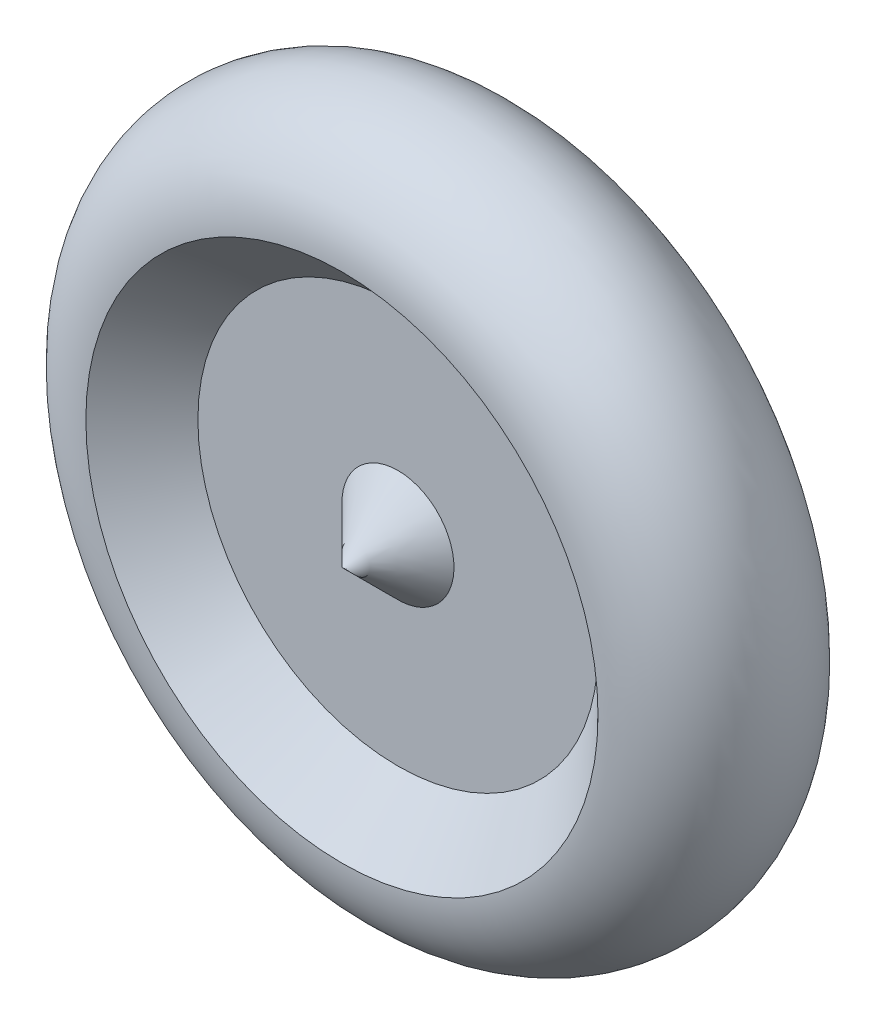
SolidWorks part; units mm, degrees
material "Plain Carbon Steel"
ref_plane "Front Plane" through (0, 0, 0) normal (0, 0, 1) x (1, 0, 0)
ref_plane "Top Plane" through (0, 0, 0) normal (0, 1, 0) x (1, 0, 0)
ref_plane "Right Plane" through (0, 0, 0) normal (1, 0, 0) x (0, 0, -1)
sketch "Sketch2" plane through (0, 0, 0) normal (1, 0, 0) x (0, 0, -1)
  line L0 (0, 0) -> (0, 123.8288) construction
  line L1 (30, 0) -> (-30, 0)
  line L2 (-30, 0) -> (-12.5, 17.5)
  line L3 (-12.5, 17.5) -> (-12.5, 62.5)
  line L4 (-12.5, 62.5) -> (-30, 80)
  line L5 (-30, 80) -> (-26.8319, 79.3853)
  line L6 (0, 110) -> (0, 0)
  line L7 (12.5, 62.5) -> (30, 80)
  line L8 (12.5, 17.5) -> (12.5, 62.5)
  line L9 (30, 0) -> (12.5, 17.5)
  arc A1 (-30, 80) -> (30, 80) centre (0, 80) cw
  point P6 (0, 0)
  point P9 (0, 0)
  point P14 (0, 0)
  point P17 (0, 0)
  point P18 (0, 0)
  point P19 (0, 0)
  point P20 (0, 0)
  dimension "D6" = 30
  dimension "D1" = 45
  dimension "D2" = 80
  dimension "D3" = 135
  dimension "D4" = 135
  dimension "D5" = 60
  dimension "D7" = 60
  dimension "D8" = 80
revolve "Revolve1" add sketch "Sketch2" angle 360 about L1
